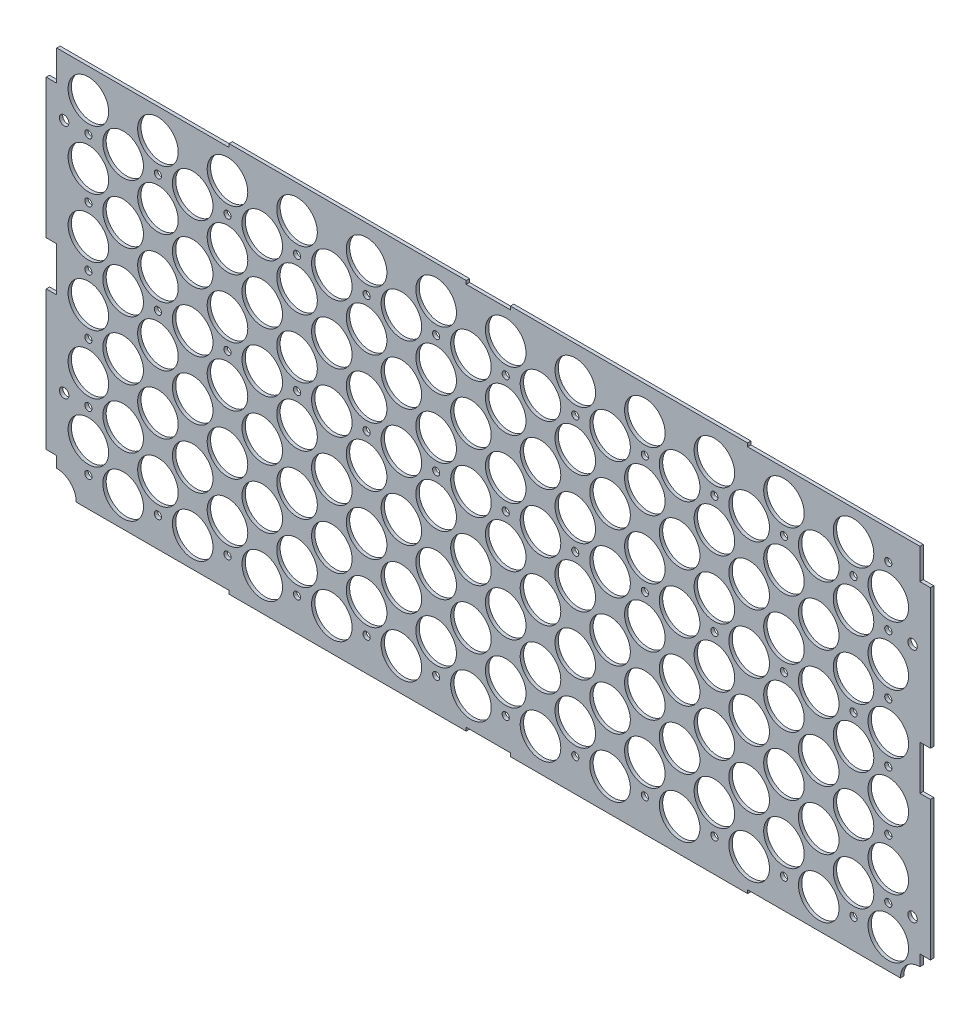
SolidWorks part; units mm, degrees
material "Circuit imprimé d'alimentation"
ref_plane "Face" through (0, 0, 0) normal (0, 0, 1) x (1, 0, 0)
ref_plane "Dessus" through (0, 0, 0) normal (0, 1, 0) x (1, 0, 0)
ref_plane "Droite" through (0, 0, 0) normal (1, 0, 0) x (0, 0, -1)
sketch "Esquisse1" plane through (0, 0, 0) normal (0, 0, 1) x (1, 0, 0)
  line L1 (-204.75, -91) -> (204.75, -91)
  line L2 (-204.75, -91) -> (-204.75, 91)
  line L3 (-204.75, 91) -> (204.75, 91)
  line L4 (204.75, -91) -> (204.75, 91)
  line L5 (-204.75, -91) -> (204.75, 91) construction
  line L6 (-204.75, 91) -> (204.75, -91) construction
  point P0 (0, 0)
  dimension "D1" = 409.5
  dimension "D2" = 182
extrude "Boss.-Extru.2" add sketch "Esquisse1" along normal mid plane 1.5875 contours L3 L4 L1 L2
ref_plane "Plan1" through (0, 0, 0) normal (0, 0, 1) x (1, 0, 0)
ref_plane "Plan2" through (0, 0, 0) normal (0, 1, 0) x (1, 0, 0)
sketch "Esquisse2" plane through (0, 0, 0) normal (0, 0, 1) x (1, 0, 0)
  line L0 (-204.75, -91) -> (204.75, -91) construction
  line L1 (-173.25, -77) -> (-173.25, -91) construction
  line L2 (-204.75, -91) -> (-204.75, 91) construction
  line L6 (-173.25, -77) -> (-173.25, -63) construction
  line L7 (-173.25, -63) -> (-189.75, -63) construction
  circle A0 centre (-173.25, -77) radius 9.625
  circle A1 centre (-189.75, -63) radius 9.625
  dimension "D1" = 19.25
  dimension "D2" = 16.5
  dimension "D3" = 14
  dimension "D5" = 14
  dimension "D4" = 15
extrude "Enlèv. mat.-Extru.2" cut sketch "Esquisse2" along normal through all both and the other way through all contours A0 | A1
pattern_linear "Répétition linéaire2" count 12 spacing 33 along (1, 0, 0) count 6 spacing 28 along (0, 1, 0) of "Enlèv. mat.-Extru.2"
sketch "Esquisse3" plane through (0, 0, -0.7937) normal (0, 0, -1) x (-1, 0, 0)
  line L1 (-189.75, -77) -> (-189.75, -49) construction
  line L2 (173.25, -77) -> (189.75, -77) construction
  line L3 (189.75, -77) -> (189.75, -63) construction
  point P4 (189.75, -77)
  point P9 (-189.75, -63)
hole_wizard "Dégagement M31" positions "Esquisse3D1" profile "Esquisse4" hole size "M3" standard "Ansi Metric" end condition through all
sketch3d "Esquisse3D1"
  point P0 (-189.75, -77, -0.7937)
  point P4 (189.75, -63, -0.7937)
sketch "Esquisse4" plane through (-189.75, -77, -0.7937) normal (1, 0, 0) x (0, 1, 0)
  line L0 (0, 0) -> (0, 1.5875)
  line L1 (0, 1.5875) -> (1.7, 1.5875)
  line L2 (1.7, 1.5875) -> (1.7, 0)
  line L5 (1.7, 0) -> (0, 0)
  line L11 (0, -6.35) -> (0, 107.95) construction
  dimension "Diamètre du perçage jusqu'au prochain" = 3.4
  dimension "Profondeur du perçage jusqu'au prochain" = 1.5875
pattern_linear "Répétition linéaire3" count 6 spacing 28 along (0, 1, 0) of "Dégagement M31"
sketch "Esquisse5" plane through (0, 0, -0.7937) normal (0, 0, -1) x (-1, 0, 0)
  line L2 (189.75, 77) -> (156.75, 77) construction
  line L3 (140.25, -77) -> (173.25, -77) construction
  line L4 (173.25, 7) -> (140.25, 7) construction
  line L5 (173.25, 63) -> (140.25, 63) construction
  point P6 (156.75, 7)
  point P12 (156.75, 63)
  point P13 (173.25, 77)
  point P16 (156.75, -77)
hole_wizard "Dégagement M32" positions "Esquisse3D2" profile "Esquisse6" hole size "M3" standard "Ansi Metric" end condition through all
sketch3d "Esquisse3D2"
  point P55 (-156.75, -77, -0.7937)
  point P67 (-156.75, 7, -0.7937)
  point P70 (-156.75, 63, -0.7937)
sketch "Esquisse6" plane through (-156.75, -77, -0.7937) normal (1, 0, 0) x (0, 1, 0)
  line L0 (0, 0) -> (0, 1.5875)
  line L1 (0, 1.5875) -> (1.7, 1.5875)
  line L2 (1.7, 1.5875) -> (1.7, 0)
  line L5 (1.7, 0) -> (0, 0)
  line L11 (0, -6.35) -> (0, 107.95) construction
  dimension "Diamètre du perçage jusqu'au prochain" = 3.4
  dimension "Profondeur du perçage jusqu'au prochain" = 1.5875
pattern_linear "Répétition linéaire4" count 11 spacing 33 along (1, 0, 0) of "Dégagement M32"
sketch "Esquisse7" plane through (0, 0, -0.7937) normal (0, 0, -1) x (-1, 0, 0)
  line L5 (204.75, -91) -> (204.75, 91) construction
  line L6 (204.75, 76.5) -> (209.75, 76.5)
  line L7 (204.75, 76.5) -> (204.75, 10.5)
  line L8 (204.75, -76.5) -> (209.75, -76.5)
  line L9 (209.75, 76.5) -> (209.75, 10.5)
  line L10 (204.75, 91) -> (-204.75, 91) construction
  line L11 (204.75, -91) -> (-204.75, -91) construction
  line L12 (0.8731, 0) -> (-0.8731, 0) construction
  line L13 (209.75, 10.5) -> (204.75, 10.5)
  line L15 (209.75, -10.5) -> (204.75, -10.5)
  line L19 (209.75, -10.5) -> (209.75, -76.5)
  line L20 (204.75, -10.5) -> (204.75, -76.5)
  point P16 (207.25, 0)
  dimension "D4" = 14.5
  dimension "D5" = 5
  dimension "D6" = 14.5
  dimension "D7" = 21
  dimension "D8" = 10.5
extrude "Boss.-Extru.3" add sketch "Esquisse7" against normal up to surface (1.5875 mm away) up to face at (171.55, -77, 0.7937)
sketch "Esquisse9" plane through (0, 0, -0.7937) normal (0, 0, -1) x (-1, 0, 0)
  line L0 (204.75, -91) -> (-204.75, -91) construction
  line L1 (-123, -91) -> (-10.5, -91)
  line L2 (-123, -91) -> (-123, -92.5875)
  line L3 (-123, -92.5875) -> (-10.5, -92.5875)
  line L4 (123, -91) -> (123, -92.5875)
  line L5 (10.5, -92.5875) -> (123, -92.5875)
  line L11 (10.5, -91) -> (10.5, -92.5875)
  line L13 (-10.5, -91) -> (-10.5, -92.5875)
  line L14 (10.5, -91) -> (123, -91)
  line L15 (0, 0.8731) -> (0, -0.8731) construction
  line L16 (-204.75, -91) -> (-204.75, 91) construction
  dimension "D1" = 246
  dimension "D2" = 1.5875
  dimension "D3" = 21
  dimension "D4" = 10.5
  dimension "D5" = 81.75
extrude "Boss.-Extru.4" add sketch "Esquisse9" against normal up to surface (1.5875 mm away) up to face at (171.55, -77, 0.7937)
mirror "Symétrie1" about plane through (0, 0, 0) normal (0, 1, 0) of "Boss.-Extru.4"
mirror "Symétrie2" about plane through (0, 0, 0) normal (1, 0, 0) of "Boss.-Extru.3"
sketch "Esquisse10" plane through (0, 0, 0.7937) normal (0, 0, 1) x (1, 0, 0)
  line L0 (207.25, 60) -> (207.25, 32.1967) construction
  line L1 (209.75, 76.5) -> (209.75, 10.5) construction
  line L2 (0.8731, 0) -> (-0.8731, 0) construction
  circle A0 centre (207.25, 60) radius 1.1906
  dimension "D1" = 2.3813
  dimension "D2" = 2.5
  dimension "D3" = 60
extrude "Enlèv. mat.-Extru.3" [suppressed] cut sketch "Esquisse10" against normal through all
pattern_linear "Répétition linéaire5" [suppressed] count 3 spacing 15
mirror "Symétrie3" [suppressed] about plane through (0, 0, 0) normal (0, 1, 0)
mirror "Symétrie4" [suppressed] about plane through (0, 0, 0) normal (1, 0, 0)
sketch "Esquisse11" plane through (0, 0, -0.7937) normal (0, 0, -1) x (-1, 0, 0)
  line L0 (189.75, -49) -> (201.25, -49) construction
  line L1 (204.75, -10.5) -> (204.75, 10.5) construction
  line L2 (-189.75, 49) -> (-173.25, 49) construction
  line L3 (-204.75, -10.5) -> (-204.75, 10.5) construction
  circle A0 centre (201.25, -49) radius 2.25
  circle A1 centre (201.25, 63) radius 2.25
  circle A3 centre (-201.25, -63) radius 2.25
  circle A4 centre (-201.25, 49) radius 2.25
  dimension "D1" = 4.5
  dimension "D2" = 3.5
  dimension "D3" = 3.5
extrude "Enlèv. mat.-Extru.4" cut sketch "Esquisse11" against normal blind 10
sketch "Esquisse12" plane through (0, 0, -0.7937) normal (0, 0, -1) x (-1, 0, 0)
  line L0 (-204.75, -81.75) -> (-204.75, -91)
  line L1 (-204.75, -91) -> (-195.5, -91)
  arc A0 (-195.5, -91) -> (-204.75, -81.75) centre (-204.75, -91) ccw
  dimension "D1" = 18.5
extrude "Enlèv. mat.-Extru.5" cut sketch "Esquisse12" against normal up to next
mirror "Symétrie5" about plane through (0, 0, 0) normal (1, 0, 0) of "Enlèv. mat.-Extru.5"
equation "\"D3@Répétition linéaire2\"=\"D2@Esquisse2\"*2"
equation "\"D4@Répétition linéaire2\"=\"D3@Esquisse2\"*2"
